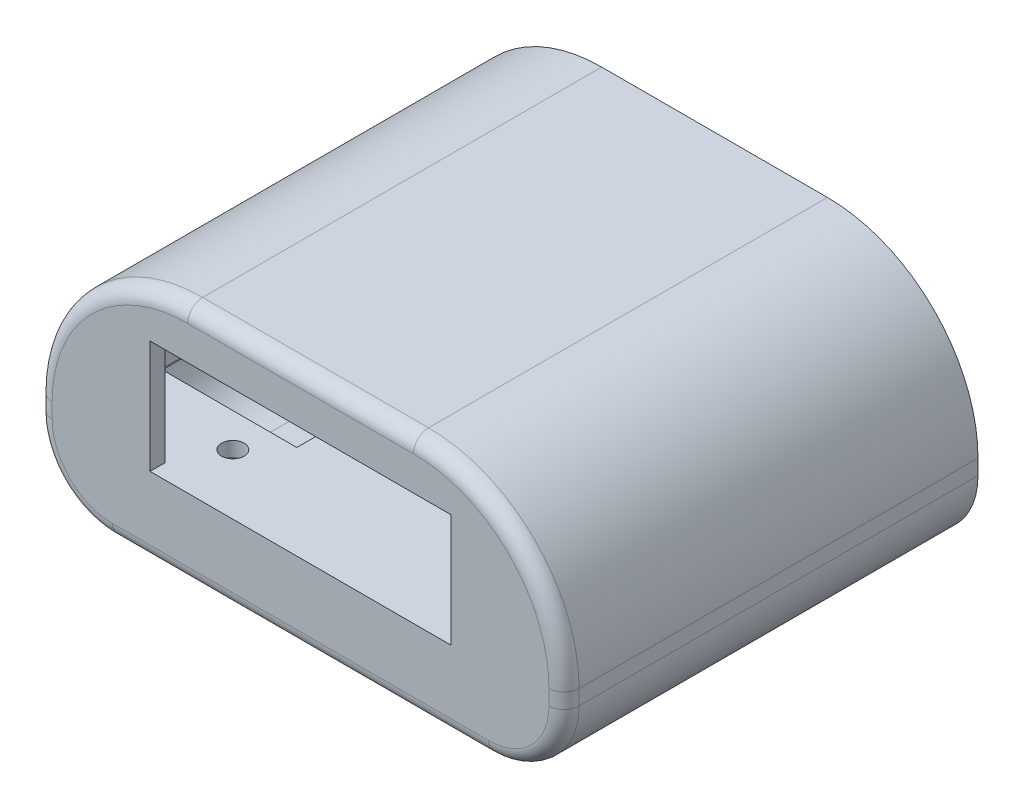
SolidWorks part; units mm, degrees
ref_plane "Front Plane" through (0, 0, 0) normal (0, 0, 1) x (1, 0, 0)
ref_plane "Top Plane" through (0, 0, 0) normal (0, 1, 0) x (1, 0, 0)
ref_plane "Right Plane" through (0, 0, 0) normal (1, 0, 0) x (0, 0, -1)
sketch "Sketch1" plane through (0, 0, 0) normal (0, 0, 1) x (1, 0, 0)
  line L1 (-15, 16) -> (15, 16)
  line L2 (-35, -4) -> (-35, -6)
  line L3 (-25, -16) -> (25, -16)
  line L4 (35, -4) -> (35, -6)
  line L5 (-35, 16) -> (35, -16) construction
  line L6 (-35, -16) -> (35, 16) construction
  arc A0 (25, -16) -> (35, -6) centre (25, -6) ccw
  arc A1 (-35, -6) -> (-25, -16) centre (-25, -6) ccw
  arc A2 (15, 16) -> (35, -4) centre (15, -4) cw
  arc A3 (-15, 16) -> (-35, -4) centre (-15, -4) ccw
  point P0 (0, 0)
  dimension "D1" = 20
  dimension "D4" = 10
  dimension "D2" = 70
  dimension "D3" = 32
extrude "Boss-Extrude1" add sketch "Sketch1" along normal blind 55
shell "Shell1" thickness 2
sketch "Sketch2" plane through (0, 0, 0) normal (0, 0, -1) x (-1, 0, 0)
  line L0 (-15, 16) -> (15, 16) construction
  line L1 (-15, 4.48) -> (-30.8773, 4.48)
  line L2 (-15, 4.48) -> (-15, 14)
  line L3 (0, 14) -> (0, -14) construction
  line L4 (-15, 14) -> (15, 14) construction
  line L5 (25, -14) -> (-25, -14) construction
  line L6 (15, 4.48) -> (15, 14)
  line L7 (15, 4.48) -> (30.8773, 4.48)
  arc A0 (-15, 14) -> (-33, -4) centre (-15, -4) ccw construction
  arc A1 (-30.8773, 4.48) -> (-15, 14) centre (-15, -4) cw
  arc A2 (30.8773, 4.48) -> (15, 14) centre (15, -4) ccw
  dimension "D1" = 11.52
extrude "Boss-Extrude2" add sketch "Sketch2" against normal blind 10 contours L7 A2 L6 | L1 A1 L2
hole_wizard "M3x0.5 Tapped Hole1" positions "Sketch3" profile "Sketch4" tap size "M3x0.5" standard "ANSI Metric"
sketch "Sketch3" plane through (0, 0, 0) normal (0, 0, -1) x (-1, 0, 0)
  line L0 (-15, 16) -> (15, 16) construction
  line L1 (-35, -6) -> (-35, -4) construction
  line L2 (35, -4) -> (35, -6) construction
  point P0 (-18.4, 8)
  point P10 (21.6, 8)
  dimension "D1" = 8
  dimension "D2" = 16.6
  dimension "D3" = 13.4
sketch "Sketch4" plane through (18.4, 8, 0) normal (1, 0, 0) x (0, 1, 0)
  line L0 (0, 0) -> (0, 8.2511)
  line L1 (0, 8.2511) -> (1.25, 7.5)
  line L2 (1.25, 7.5) -> (1.25, 0)
  line L5 (1.25, 0) -> (0, 0)
  line L10 (0, 8.2511) -> (-1.25, 7.5) construction
  line L11 (0, -6.35) -> (0, 107.95) construction
  dimension "Tap Drill Dia." = 2.5
  dimension "Tap Drill Depth" = 7.5
  dimension "Drill Angle" = 118
sketch "Sketch5" plane through (0, 0, 0) normal (0, 0, -1) x (-1, 0, 0)
  line L1 (-33, -5.52) -> (33, -5.52)
  line L2 (-33, -5.52) -> (-33, -7.52)
  line L3 (-33, -7.52) -> (33, -7.52)
  line L4 (33, -5.52) -> (33, -7.52)
  line L5 (33, -4) -> (33, -6) construction
  line L7 (-15, 16) -> (15, 16) construction
  dimension "D1" = 21.52
  dimension "D2" = 2
extrude "Boss-Extrude3" add sketch "Sketch5" against normal up to next contours L1 L4 L3 L2
sketch "Sketch6" plane through (0, 0, 53) normal (0, 0, -1) x (-1, 0, 0)
  line L0 (-33, -5.52) -> (33, -5.52) construction
  line L1 (-20, -5.52) -> (20, -5.52)
  line L2 (-20, -5.52) -> (-20, 9.48)
  line L3 (-20, 9.48) -> (20, 9.48)
  line L4 (20, -5.52) -> (20, 9.48)
  point P6 (0, 9.48)
  dimension "D1" = 15
  dimension "D2" = 40
extrude "Cut-Extrude1" cut sketch "Sketch6" against normal blind 10
hole_wizard "Ø3.0mm Dowel Hole1" positions "Sketch7" profile "Sketch8" hole size "Ø3.0" standard "AS"
sketch "Sketch7" plane through (0, -5.52, 0) normal (0, 1, 0) x (1, 0, 0)
  line L0 (17, -34.5) -> (-17, -47) construction
  line L2 (-20, -55) -> (20, -55) construction
  line L3 (-17, -47) -> (-17, -22) construction
  point P0 (-17, -47)
  point P2 (-17, -22)
  point P4 (17, -34.5)
  point P11 (0, -40.75)
  point P14 (0, -55)
  point P20 (-17, -34.5)
  dimension "D1" = 25
  dimension "D2" = 34
  dimension "D3" = 8
sketch "Sketch8" plane through (-17, -5.52, 47) normal (1, 0, 0) x (0, 0, 1)
  line L0 (0, 0) -> (0, 4.9013)
  line L1 (0, 4.9013) -> (1.5, 4)
  line L2 (1.5, 4) -> (1.5, 0)
  line L5 (1.5, 0) -> (0, 0)
  line L10 (0, 4.9013) -> (-1.5, 4) construction
  line L11 (0, -6.35) -> (0, 107.95) construction
  dimension "Hole Dia." = 3
  dimension "Hole Depth" = 4
  dimension "Drill Angle" = 118
sketch "Sketch9" plane through (0, -5.52, 0) normal (0, 1, 0) x (1, 0, 0)
  line L0 (-33, -53) -> (-33, 0) construction
  line L1 (-33, -26.5) -> (-13, -26.5)
  line L2 (-33, -26.5) -> (-33, -42.5)
  line L3 (-33, -42.5) -> (-13, -42.5)
  line L4 (-13, -26.5) -> (-13, -42.5)
  line L5 (-17, -47) -> (-17, -22) construction
  point P6 (-17, -34.5)
  point P7 (-13, -34.5)
  dimension "D1" = 20
extrude "Cut-Extrude2" cut sketch "Sketch9" against normal up to surface (2 mm away) up to face at (-17, -7.52, 45.5)
fillet "Fillet1" radius 2 8 edges at (35, -5, 55) (32.0711, -13.0711, 55) (0, -16, 55) (-32.0711, -13.0711, 55) (-35, -5, 55) (-29.1421, 10.1421, 55) (0, 16, 55) (29.1421, 10.1421, 55)
